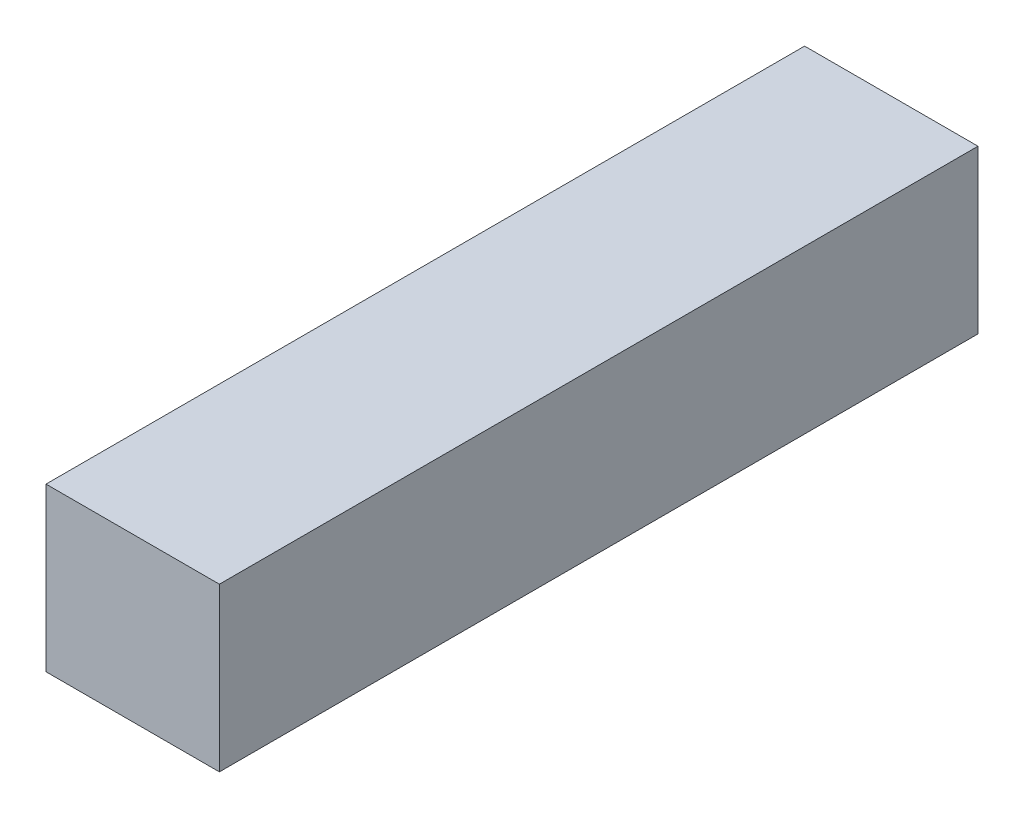
SolidWorks part; units mm, degrees
ref_plane "前视基准面" through (0, 0, 0) normal (0, 0, 1) x (1, 0, 0)
ref_plane "上视基准面" through (0, 0, 0) normal (0, 1, 0) x (1, 0, 0)
ref_plane "右视基准面" through (0, 0, 0) normal (1, 0, 0) x (0, 0, -1)
other "Configuration Table"
sketch "草图1" plane through (0, 0, 0) normal (0, 0, 1) x (1, 0, 0)
  line L1 (-32, 30) -> (32, 30)
  line L2 (-32, 30) -> (-32, -30)
  line L3 (-32, -30) -> (32, -30)
  line L4 (32, 30) -> (32, -30)
  line L5 (-32, 30) -> (32, -30) construction
  line L6 (-32, -30) -> (32, 30) construction
  point P0 (0, 0)
  point P6 (0, 0)
extrude "凸台-拉伸1" add sketch "草图1" along normal blind 280
